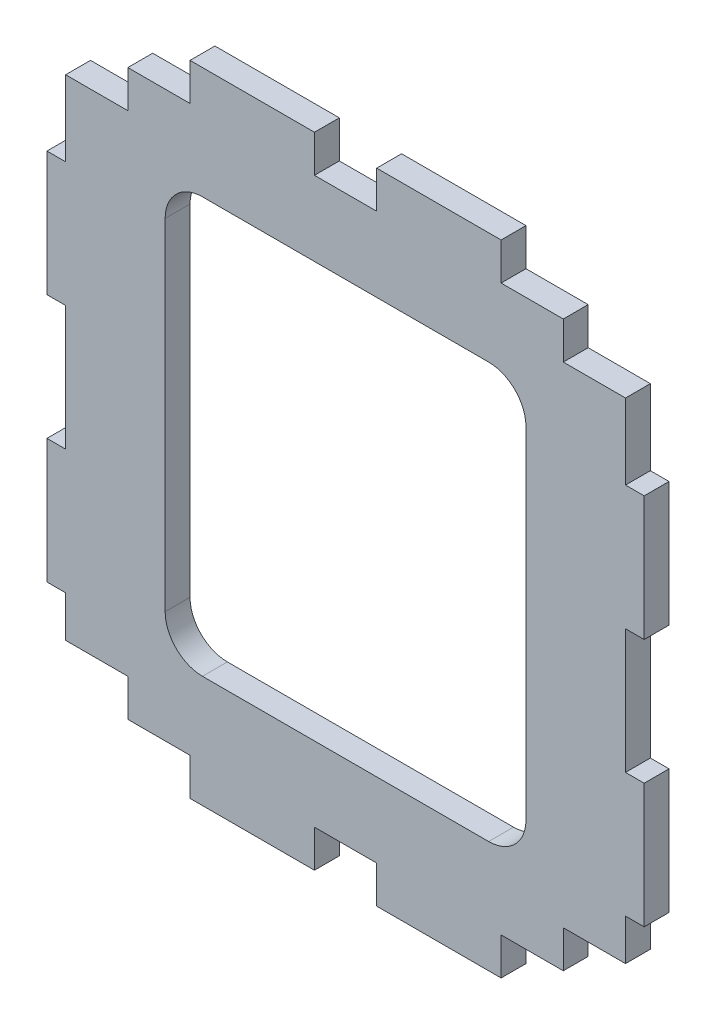
SolidWorks part; units mm, degrees
ref_plane "前视基准面" through (0, 0, 0) normal (0, 0, 1) x (1, 0, 0)
ref_plane "上视基准面" through (0, 0, 0) normal (0, 1, 0) x (1, 0, 0)
ref_plane "右视基准面" through (0, 0, 0) normal (1, 0, 0) x (0, 0, -1)
sketch "Model" plane through (0, 0, 0) normal (0, 0, 1) x (1, 0, 0)
  line L0 (682.1514, 151.3427) -> (685.1514, 151.3427)
  line L1 (685.1514, 151.3427) -> (685.1514, 154.3427)
  line L2 (685.1514, 154.3427) -> (690.1514, 154.3427)
  line L3 (690.1514, 154.3427) -> (690.1514, 157.3427)
  line L4 (690.1514, 157.3427) -> (700.1514, 157.3427)
  line L5 (700.1514, 157.3427) -> (700.1514, 154.3427)
  line L6 (700.1514, 154.3427) -> (705.1514, 154.3427)
  line L7 (705.1514, 154.3427) -> (705.1514, 157.3427)
  line L8 (705.1514, 157.3427) -> (715.1514, 157.3427)
  line L9 (715.1514, 157.3427) -> (715.1514, 154.3427)
  line L10 (715.1514, 154.3427) -> (720.1514, 154.3427)
  line L11 (726.6514, 115.2827) -> (725.1514, 115.2827)
  line L12 (725.1514, 115.2827) -> (725.1514, 111.9727)
  line L13 (725.1514, 111.9727) -> (720.1514, 111.9727)
  line L14 (720.1514, 111.9727) -> (720.1514, 108.9727)
  line L15 (680.1514, 145.2827) -> (678.6514, 145.2827)
  line L16 (678.6514, 145.2827) -> (678.6514, 135.2827)
  line L17 (678.6514, 135.2827) -> (680.1514, 135.2827)
  line L18 (680.1514, 125.2827) -> (678.6514, 125.2827)
  line L19 (678.6514, 125.2827) -> (678.6514, 115.2827)
  line L20 (678.6514, 115.2827) -> (680.1514, 115.2827)
  line L21 (680.1514, 115.2827) -> (680.1514, 111.9727)
  line L22 (680.1514, 111.9727) -> (685.1514, 111.9727)
  line L23 (685.1514, 111.9727) -> (685.1514, 108.9727)
  line L24 (685.1514, 108.9727) -> (690.1514, 108.9727)
  line L25 (690.1514, 108.9727) -> (690.1514, 105.9727)
  line L26 (690.1514, 105.9727) -> (700.1514, 105.9727)
  line L27 (700.1514, 105.9727) -> (700.1514, 108.9727)
  line L28 (700.1514, 108.9727) -> (705.1514, 108.9727)
  line L29 (705.1514, 108.9727) -> (705.1514, 105.9727)
  line L30 (705.1514, 105.9727) -> (715.1514, 105.9727)
  line L31 (715.1514, 105.9727) -> (715.1514, 108.9727)
  line L32 (715.1514, 108.9727) -> (720.1514, 108.9727)
  line L33 (714.1514, 148.3427) -> (691.1514, 148.3427)
  line L34 (717.1514, 145.3427) -> (717.1514, 117.9727)
  line L35 (714.1514, 114.9727) -> (691.1514, 114.9727)
  line L36 (688.1514, 145.3427) -> (688.1514, 117.9727)
  line L37 (680.1514, 130.0727) -> (680.1514, 125.2827)
  line L38 (680.1514, 130.0727) -> (680.1514, 135.2827)
  line L39 (682.1514, 151.3427) -> (680.1514, 151.3427)
  line L40 (680.1514, 145.2827) -> (680.1514, 151.3427)
  line L41 (723.1514, 151.3427) -> (720.1514, 151.3427)
  line L42 (720.1514, 151.3427) -> (720.1514, 154.3427)
  line L43 (725.1514, 145.2827) -> (726.6514, 145.2827)
  line L44 (726.6514, 145.2827) -> (726.6514, 135.2827)
  line L45 (726.6514, 135.2827) -> (725.1514, 135.2827)
  line L46 (725.1514, 125.2827) -> (726.6514, 125.2827)
  line L47 (726.6514, 125.2827) -> (726.6514, 115.2827)
  line L48 (725.1514, 130.0727) -> (725.1514, 125.2827)
  line L49 (725.1514, 130.0727) -> (725.1514, 135.2827)
  line L50 (723.1514, 151.3427) -> (725.1514, 151.3427)
  line L51 (725.1514, 145.2827) -> (725.1514, 151.3427)
  arc A0 (691.1514, 148.3427) -> (688.1514, 145.3427) centre (691.1514, 145.3427) ccw
  arc A1 (717.1514, 145.3427) -> (714.1514, 148.3427) centre (714.1514, 145.3427) ccw
  arc A2 (714.1514, 114.9727) -> (717.1514, 117.9727) centre (714.1514, 117.9727) ccw
  arc A3 (688.1514, 117.9727) -> (691.1514, 114.9727) centre (691.1514, 117.9727) ccw
extrude "凸台-拉伸1" add sketch "Model" along normal blind 2
